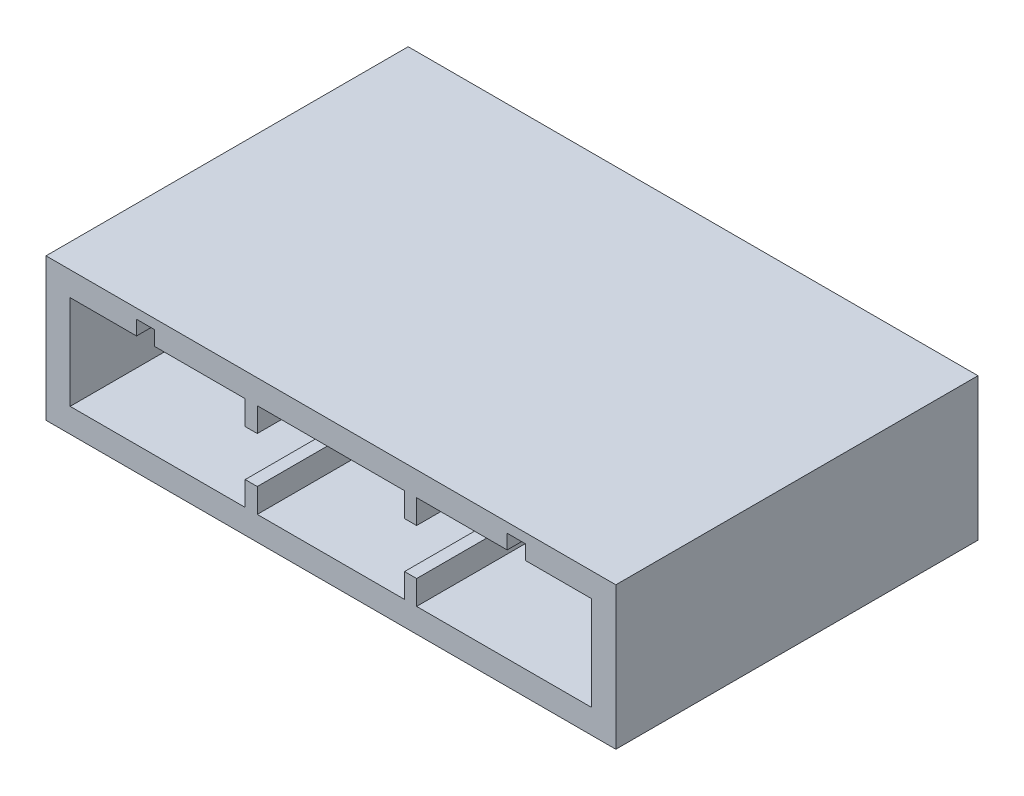
SolidWorks part; units mm, degrees
ref_plane "Alzado" through (0, 0, 0) normal (0, 0, 1) x (1, 0, 0)
ref_plane "Planta" through (0, 0, 0) normal (0, 1, 0) x (1, 0, 0)
ref_plane "Vista lateral" through (0, 0, 0) normal (1, 0, 0) x (0, 0, -1)
sketch "Croquis1" plane through (0, 0, 0) normal (0, 0, 1) x (1, 0, 0)
  line L0 (-21.6, -12.8603) -> (-21.6, -14.8603) construction
  line L1 (-21.6, -5.0603) -> (21.6, -5.0603)
  line L2 (-21.6, -5.0603) -> (-21.6, -12.8603)
  line L3 (-21.6, -12.8603) -> (21.6, -12.8603)
  line L4 (21.6, -5.0603) -> (21.6, -12.8603)
  line L5 (-21.6, -14.8603) -> (-23.6, -14.8603) construction
  line L7 (-23.6, -14.8603) -> (23.6, -14.8603)
  line L8 (-23.6, -14.8603) -> (-23.6, -3.0603)
  line L9 (-23.6, -3.0603) -> (23.6, -3.0603)
  line L10 (23.6, -14.8603) -> (23.6, -3.0603)
  point P5 (0, -5.0603)
  dimension "D1" = 43.2
  dimension "D2" = 7.8
  dimension "D3" = 2
  dimension "D4" = 2
  dimension "D5" = 47.2
  dimension "D6" = 11.8
extrude "Saliente-Extruir1" add sketch "Croquis1" along normal blind 20
sketch "Croquis2" plane through (0, 0, 20) normal (0, 0, 1) x (1, 0, 0)
  line L0 (-21.6, -5.0603) -> (-16.1, -5.0603) construction
  line L1 (21.6, -5.0603) -> (-21.6, -5.0603) construction
  line L2 (-16.1, -5.0603) -> (-16.1, -3.8603)
  line L3 (-16.1, -3.8603) -> (-14.6, -3.8603)
  line L4 (-14.6, -3.8603) -> (-14.6, -5.0603)
  line L5 (-14.6, -5.0603) -> (-16.1, -5.0603)
  line L6 (21.6, -5.0603) -> (16.1, -5.0603) construction
  line L7 (16.1, -5.0603) -> (16.1, -3.8603)
  line L8 (16.1, -3.8603) -> (14.6, -3.8603)
  line L9 (14.6, -3.8603) -> (14.6, -5.0603)
  line L10 (14.6, -5.0603) -> (16.1, -5.0603)
  dimension "D1" = 5.5
  dimension "D2" = 1.2
  dimension "D3" = 1.5
  dimension "D4" = 5.5
  dimension "D5" = 1.5
extrude "Cortar-Extruir1" cut sketch "Croquis2" against normal blind 20
sketch "Croquis3" plane through (0, 0, 20) normal (0, 0, 1) x (1, 0, 0)
  line L0 (-21.6, -5.0603) -> (-7.1, -5.0603) construction
  line L1 (14.6, -5.0603) -> (-14.6, -5.0603) construction
  line L2 (-7.1, -5.0603) -> (-7.1, -7.0603)
  line L3 (-7.1, -7.0603) -> (-6.1, -7.0603)
  line L4 (-6.1, -7.0603) -> (-6.1, -5.0603)
  line L5 (-6.1, -5.0603) -> (-7.1, -5.0603)
  line L6 (21.6, -5.0603) -> (7.1, -5.0603) construction
  line L7 (7.1, -5.0603) -> (7.1, -7.0603)
  line L8 (7.1, -7.0603) -> (6.1, -7.0603)
  line L9 (6.1, -7.0603) -> (6.1, -5.0603)
  line L10 (6.1, -5.0603) -> (7.1, -5.0603)
  line L11 (-7.1, -12.8603) -> (-7.1, -10.8603)
  line L12 (-21.6, -12.8603) -> (21.6, -12.8603) construction
  line L13 (-7.1, -10.8603) -> (-6.1, -10.8603)
  line L14 (-6.1, -10.8603) -> (-6.1, -12.8603)
  line L15 (-6.1, -12.8603) -> (-7.1, -12.8603)
  line L16 (6.1, -12.8603) -> (6.1, -10.8603)
  line L17 (6.1, -10.8603) -> (7.1, -10.8603)
  line L18 (7.1, -10.8603) -> (7.1, -12.8603)
  line L19 (7.1, -12.8603) -> (6.1, -12.8603)
  dimension "D1" = 14.5
  dimension "D2" = 2
  dimension "D3" = 1
  dimension "D4" = 14.5
  dimension "D5" = 1
  dimension "D6" = 2
extrude "Saliente-Extruir2" add sketch "Croquis3" against normal blind 20 separate body
sketch "Croquis5" plane through (0, 0, 0) normal (0, 0, -1) x (-1, 0, 0)
  line L0 (-23.6, -3.0603) -> (-23.6, -14.8603)
  line L1 (-23.6, -14.8603) -> (23.6, -14.8603)
  line L2 (23.6, -14.8603) -> (23.6, -3.0603)
  line L3 (23.6, -3.0603) -> (-23.6, -3.0603)
extrude "Saliente-Extruir3" add sketch "Croquis5" along normal blind 10
sketch "Croquis6" plane through (0, 0, 0) normal (0, 0, 1) x (1, 0, 0)
  circle A0 centre (-4.6855, -10.0553) radius 0.8
  circle A1 centre (2.4955, -8.7821) radius 0.8
  dimension "D1" = 1.6
  dimension "D2" = 1.6
extrude "Cortar-Extruir2" cut sketch "Croquis6" against normal blind 10
